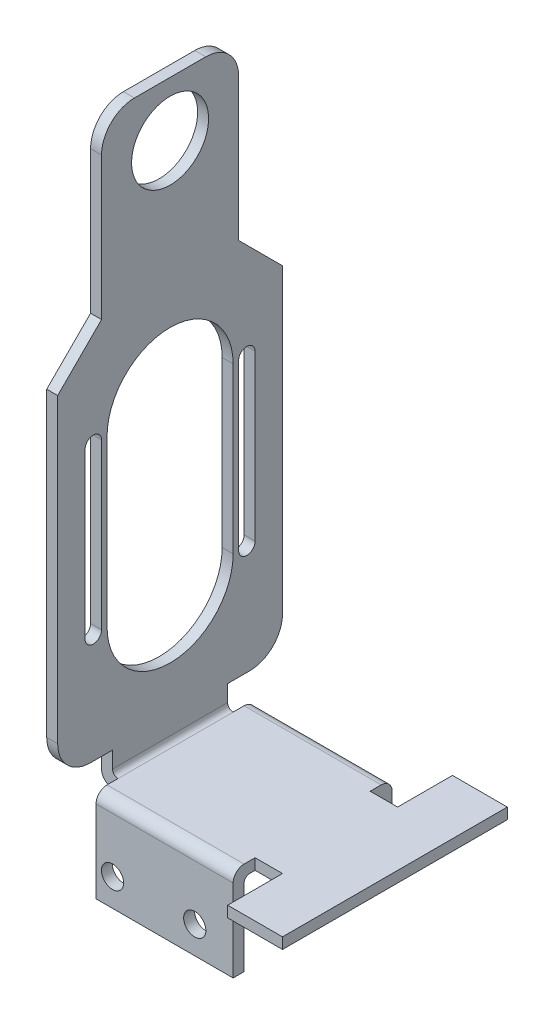
SolidWorks part; units mm, degrees
material "AISI 304"
ref_plane "Front Plane" through (0, 0, 0) normal (0, 0, 1) x (1, 0, 0)
ref_plane "Top Plane" through (0, 0, 0) normal (0, 1, 0) x (1, 0, 0)
ref_plane "Right Plane" through (0, 0, 0) normal (1, 0, 0) x (0, 0, -1)
sketch "Sketch1" plane through (0, 0, 0) normal (0, 1, 0) x (1, 0, 0)
  line L1 (-12.5, 12.5) -> (12.5, 12.5)
  line L2 (-12.5, 12.5) -> (-12.5, -12.5)
  line L3 (-12.5, -12.5) -> (12.5, -12.5)
  line L4 (12.5, 12.5) -> (12.5, -12.5)
  line L5 (-12.5, 12.5) -> (12.5, -12.5) construction
  line L6 (-12.5, -12.5) -> (12.5, 12.5) construction
  point P0 (0, 0)
  dimension "D1" = 25
  dimension "D2" = 25
extrude "Boss-Extrude1" add sketch "Sketch1" along normal blind 2
sketch "Sketch2" plane through (0, 0, 0) normal (0, -1, 0) x (1, 0, 0)
  line L0 (-12.5, 12.5) -> (-12.5, 14.5)
  line L1 (-12.5, 14.5) -> (12.5, 14.5)
  line L2 (12.5, 14.5) -> (12.5, 12.5)
  line L3 (12.5, 12.5) -> (-12.5, 12.5)
  line L4 (-28.5011, 0) -> (22.3998, 0) construction
  line L5 (12.5, -14.5) -> (12.5, -12.5)
  line L6 (-12.5, -14.5) -> (12.5, -14.5)
  line L7 (-12.5, -12.5) -> (-12.5, -14.5)
  line L8 (12.5, -12.5) -> (-12.5, -12.5)
  dimension "D1" = 2
extrude "Boss-Extrude2" add sketch "Sketch2" along normal blind 15 and the other way blind 2
sketch "Sketch3" plane through (0, 0, 14.5) normal (0, 0, 1) x (1, 0, 0)
  line L0 (-12.5, -15) -> (-12.5, 0) construction
  line L1 (-12.5, 0) -> (16.9538, 0) construction
  line L2 (-16.2457, -10) -> (16.454, -10) construction
  line L3 (12.5, -15) -> (-12.5, -15) construction
  circle A0 centre (-9.5, -10) radius 2.025
  circle A1 centre (5.5, -10) radius 2.025
  dimension "D2" = 4.05
  dimension "D3" = 4.05
  dimension "D1" = 5
  dimension "D4" = 15
  dimension "D5" = 3
extrude "Cut-Extrude1" cut sketch "Sketch3" against normal through all
fillet "Fillet1" radius 2 2 edges at (0, 2, 14.5) (0, 2, -14.5)
fillet "Fillet2" radius 1 2 edges at (0, 0, -12.5) (0, 0, 12.5)
sketch "Sketch4" plane through (-12.5, 0, 0) normal (-1, 0, 0) x (0, 0, 1)
  line L0 (-10.5, 0) -> (-10.5, 2)
  line L1 (-11.5, 0) -> (11.5, 0) construction
  line L2 (-12.5, 2) -> (12.5, 2) construction
  line L3 (-10.5, 2) -> (10.5, 2)
  line L4 (10.5, 2) -> (10.5, 0)
  line L5 (10.5, 0) -> (-10.5, 0)
  line L6 (-14.5, 0) -> (-14.5, -15) construction
  line L7 (14.5, 0) -> (14.5, -15) construction
  dimension "D1" = 4
  dimension "D2" = 4
extrude "Boss-Extrude3" add sketch "Sketch4" along normal blind 3
sketch "Sketch5" plane through (12.5, 0, 0) normal (1, 0, 0) x (0, 0, -1)
  line L0 (-10.5, 2) -> (-10.5, 0)
  line L1 (-12.5, 2) -> (12.5, 2) construction
  line L2 (-11.5, 0) -> (11.5, 0) construction
  line L3 (-10.5, 0) -> (10.5, 0)
  line L4 (10.5, 0) -> (10.5, 2)
  line L5 (10.5, 2) -> (-10.5, 2)
  line L6 (-14.5, 0) -> (-14.5, -15) construction
  line L7 (14.5, 0) -> (14.5, -15) construction
  dimension "D1" = 4
  dimension "D2" = 4
extrude "Boss-Extrude4" add sketch "Sketch5" along normal blind 15
sketch "Sketch6" plane through (0, 0, 10.5) normal (0, 0, 1) x (1, 0, 0)
  line L0 (27.5, 2) -> (27.5, 0)
  line L1 (27.5, 0) -> (17.5, 0)
  line L2 (27.5, 0) -> (12.5, 0) construction
  line L3 (17.5, 0) -> (17.5, 2)
  line L4 (27.5, 2) -> (12.5, 2) construction
  line L5 (17.5, 2) -> (27.5, 2)
  dimension "D1" = 10
extrude "Boss-Extrude5" add sketch "Sketch6" along normal blind 15 and the other way blind 36
sketch "Sketch7" plane through (0, 2, 0) normal (0, 1, 0) x (1, 0, 0)
  line L0 (-15.5, 20.5) -> (-13.5, 20.5)
  line L2 (-13.5, 20.5) -> (-13.5, -20.5)
  line L4 (-13.5, -20.5) -> (-15.5, -20.5)
  line L5 (-15.5, -20.5) -> (-15.5, 20.5)
  line L6 (-12.5, 12.5) -> (-12.5, 10.5) construction
  line L7 (-15.5, 10.5) -> (-12.5, 10.5) construction
  line L8 (-15.5, -10.5) -> (-12.5, -10.5) construction
  dimension "D1" = 3
  dimension "D2" = 2
  dimension "D3" = 10
  dimension "D4" = 10
extrude "Boss-Extrude6" add sketch "Sketch7" along normal blind 105
sketch "Sketch8" plane through (-13.5, 0, 0) normal (1, 0, 0) x (0, 0, -1)
  line L0 (-20.5, 6) -> (-10.5, 6)
  line L1 (-20.5, 107) -> (-20.5, 2) construction
  line L2 (-10.5, 6) -> (-10.5, 2)
  line L3 (-10.5, 2) -> (-20.5, 2)
  line L4 (-20.5, 2) -> (-20.5, 6)
  line L5 (0, -2.4971) -> (0, 10.2374) construction
  line L6 (10.5, 2) -> (20.5, 2)
  line L7 (10.5, 6) -> (10.5, 2)
  line L8 (20.5, 6) -> (10.5, 6)
  line L9 (20.5, 2) -> (20.5, 6)
  dimension "D1" = 4
extrude "Cut-Extrude2" cut sketch "Sketch8" against normal through all
fillet "Fillet3" radius 1 1 edges at (-13.5, 2, 0)
fillet "Fillet4" radius 2 1 edges at (-15.5, 0, 0)
sketch "Sketch10" plane through (-15.5, 0, 0) normal (-1, 0, 0) x (0, 0, 1)
  line L0 (0, -10.3411) -> (0, 99.138) construction
  line L2 (0, 56) -> (0, 26) construction
  line L3 (11.5, 56) -> (11.5, 26)
  line L4 (-11.5, 56) -> (-11.5, 26)
  line L5 (10.5, 6) -> (20.5, 6) construction
  line L6 (-27.3022, 56) -> (27.7253, 56) construction
  line L7 (-28.8794, 26) -> (22.1174, 26) construction
  line L8 (-14, 56) -> (-14, 26) construction
  line L9 (-12.4975, 56) -> (-12.4975, 26)
  line L10 (-15.5025, 56) -> (-15.5025, 26)
  line L11 (14, 56) -> (14, 26) construction
  line L12 (12.4975, 56) -> (12.4975, 26)
  line L13 (15.5025, 56) -> (15.5025, 26)
  arc A5 (-12.4975, 56) -> (-15.5025, 56) centre (-14, 56) ccw
  arc A6 (11.5, 56) -> (-11.5, 56) centre (0, 56) ccw
  arc A7 (-11.5, 26) -> (11.5, 26) centre (0, 26) ccw
  arc A8 (-15.5025, 26) -> (-12.4975, 26) centre (-14, 26) ccw
  arc A9 (12.4975, 56) -> (15.5025, 56) centre (14, 56) cw
  arc A10 (15.5025, 26) -> (12.4975, 26) centre (14, 26) cw
  point P3 (0, 41)
  point P18 (-14, 41)
  point P23 (-15.2102, 56)
  point P26 (14, 41)
  dimension "D1" = 11.5
  dimension "D4" = 1.5025
  dimension "D2" = 30
  dimension "D3" = 20
  dimension "D5" = 14
extrude "Cut-Extrude3" cut sketch "Sketch10" against normal through all
sketch "Sketch12" plane through (-15.5, 0, 0) normal (-1, 0, 0) x (0, 0, 1)
  line L0 (0, -9.8641) -> (0, 116.677) construction
  line L1 (-20.5, 107) -> (20.5, 107) construction
  circle A0 centre (0, 97) radius 7.025
  dimension "D1" = 14.05
  dimension "D2" = 10
extrude "Cut-Extrude4" cut sketch "Sketch12" against normal through all
sketch "Sketch13" plane through (-15.5, 0, 0) normal (-1, 0, 0) x (0, 0, 1)
  line L0 (0, 105.678) -> (0, -7.4302) construction
  line L1 (-20.5, 107) -> (-20.5, 67)
  line L2 (-20.5, 107) -> (-20.5, 6) construction
  line L3 (-20.5, 67) -> (-12.5, 75)
  line L4 (-12.5, 75) -> (-12.5, 107)
  line L5 (-20.5, 107) -> (20.5, 107) construction
  line L6 (-12.5, 107) -> (-20.5, 107)
  line L7 (12.5, 75) -> (12.5, 107)
  line L8 (20.5, 67) -> (12.5, 75)
  line L9 (20.5, 107) -> (20.5, 67)
  line L10 (12.5, 107) -> (20.5, 107)
  dimension "D1" = 40
  dimension "D2" = 8
  dimension "D3" = 45
extrude "Cut-Extrude5" cut sketch "Sketch13" against normal through all
fillet "Fillet7" radius 6 2 edges at (-14.5, 107, -12.5) (-14.5, 107, 12.5)
fillet "Fillet8" radius 6 2 edges at (-14.5, 6, -20.5) (-14.5, 6, 20.5)
sketch "Sketch14" plane through (0, 2, 0) normal (0, 1, 0) x (1, 0, 0)
  line L0 (17.5, 25.5) -> (27.5, 25.5)
  line L1 (27.5, 25.5) -> (27.5, 20.5)
  line L2 (27.5, 25.5) -> (27.5, -25.5) construction
  line L3 (27.5, 20.5) -> (17.5, 20.5)
  line L4 (17.5, 25.5) -> (17.5, 10.5) construction
  line L5 (17.5, 20.5) -> (17.5, 25.5)
  line L6 (0, 0) -> (37.7541, 0) construction
  line L7 (27.5, -20.5) -> (17.5, -20.5)
  line L8 (27.5, -25.5) -> (27.5, -20.5)
  line L9 (17.5, -25.5) -> (27.5, -25.5)
  line L10 (17.5, -20.5) -> (17.5, -25.5)
  dimension "D1" = 5
extrude "Cut-Extrude6" cut sketch "Sketch14" against normal through all
